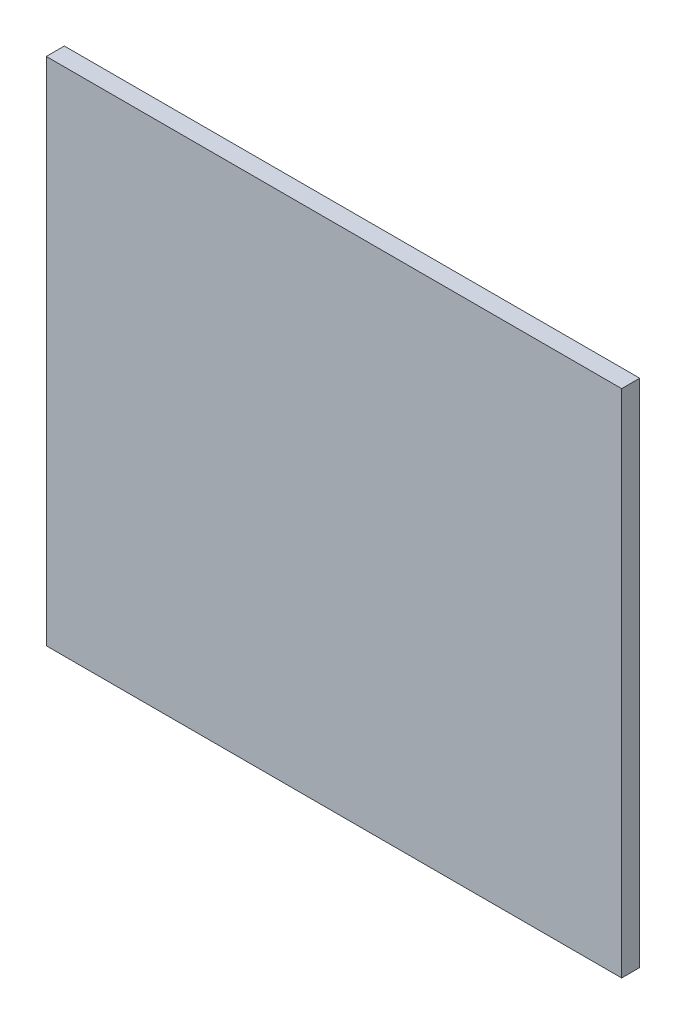
SolidWorks part; units mm, degrees
material "Гипс"
ref_plane "Спереди" through (0, 0, 0) normal (0, 0, 1) x (1, 0, 0)
ref_plane "Сверху" through (0, 0, 0) normal (0, 1, 0) x (1, 0, 0)
ref_plane "Справа" through (0, 0, 0) normal (1, 0, 0) x (0, 0, -1)
sketch "Эскиз1" plane through (0, 0, 0) normal (0, 0, 1) x (1, 0, 0)
  line L0 (-900, -353.5) -> (-400, -353.5) construction
  line L1 (-400, 0) -> (-1.5, 0)
  line L2 (-400, 0) -> (-400, -353.5)
  line L3 (-400, -353.5) -> (-1.5, -353.5)
  line L4 (-1.5, 0) -> (-1.5, -353.5)
  point P6 (0, 0)
  point P7 (0, 0)
extrude "Бобышка-Вытянуть1" add sketch "Эскиз1" against normal blind 12.5
